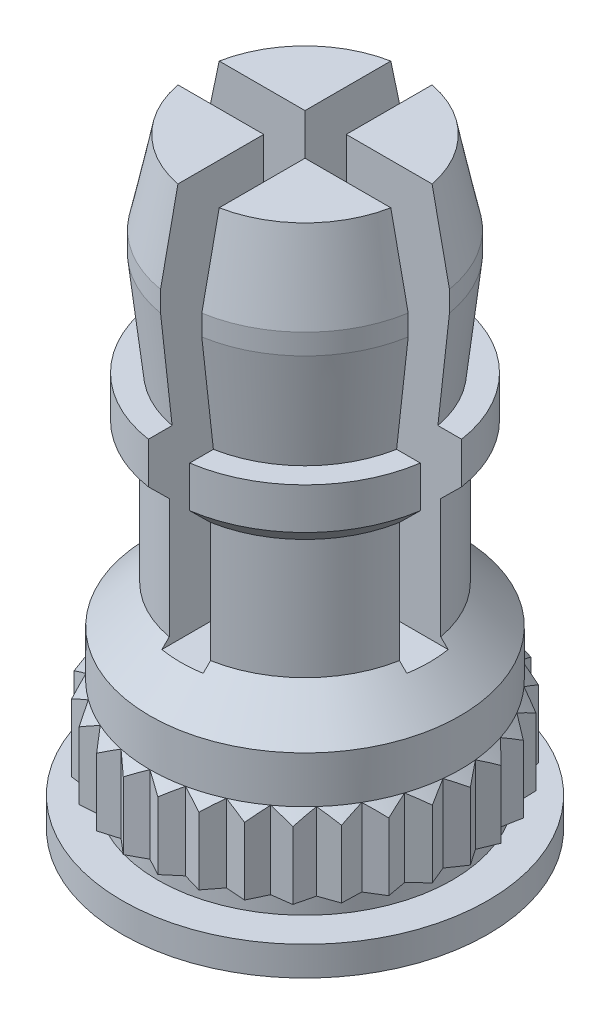
SolidWorks part; units mm, degrees
revolve "Body" add sketch "BodySke" angle 360 about L9
sketch "BodySke" plane through (0, 0, 0) normal (0, 0, 1) x (1, 0, 0)
  line L0 (2.5578, 0) -> (2.5578, 0.381)
  line L1 (2.6924, 2.5354) -> (2.0295, 3.1984)
  line L2 (2.8702, 1.5494) -> (2.6924, 1.7272)
  line L3 (2.0295, 3.1984) -> (2.0295, 5.2756)
  line L4 (0, -0.508) -> (3.175, -0.508)
  line L5 (3.175, -0.508) -> (3.175, 0)
  line L6 (3.175, 0) -> (2.5578, 0)
  line L7 (2.3876, 5.6337) -> (2.3876, 6.35)
  line L8 (2.6924, 1.7272) -> (2.6924, 2.5354)
  line L9 (0, -0.508) -> (0, 17.145) construction
  line L10 (2.3876, 6.35) -> (1.9812, 6.35)
  line L11 (1.9812, 6.35) -> (2.1793, 8.1407)
  line L12 (2.1793, 8.1407) -> (2.1793, 8.4988)
  line L13 (2.1793, 8.4988) -> (1.8821, 9.9314)
  line L14 (1.8821, 9.9314) -> (0, 9.9314)
  line L15 (2.5578, 0.381) -> (2.8702, 0.381)
  line L16 (2.8702, 0.381) -> (2.8702, 1.5494)
  line L17 (0, 9.9314) -> (0, -0.508)
  line L19 (2.3876, 5.6337) -> (2.0295, 5.2756)
  dimension "H_dia" = 6.35
  dimension "C_dia" = 5.3848
  dimension "Clinch_dia" = 5.7404
  dimension "Groove_dia" = 5.1156
  dimension "T_ht" = 0.508
  dimension "Groove_wid" = 0.381
  dimension "Clinch_lim" = 1.3462
  dimension "Length" = 6.35
  dimension "D_ht" = 3.5814
  dimension "D4" = 45
  dimension "Neck_dia" = 4.0589
  dimension "B_dia" = 4.7752
  dimension "B_ht" = 0.7163
  dimension "Panel_dia" = 3.9624
  dimension "Slip_dia" = 4.3586
  dimension "Tip_dia" = 3.7643
  dimension "Grip_ht" = 1.7907
  dimension "Slip_ht" = 0.3581
  dimension "Neck_len" = 3.1516
ref_plane "Plane1" through (0, 0, 0) normal (0, 0, 1) x (1, 0, 0)
ref_plane "Plane2" through (0, 0, 0) normal (0, 1, 0) x (1, 0, 0)
ref_plane "Plane3" through (0, 0, 0) normal (1, 0, 0) x (0, 0, -1)
sketch "SlitCutSke" plane through (0, 9.9314, 0) normal (0, 1, 0) x (-1, 0, 0)
  line L0 (-2.6685, 0.3581) -> (2.6685, 0.3581)
  line L1 (2.6685, -0.3581) -> (-2.6685, -0.3581)
  line L2 (-2.6685, 0.3581) -> (-2.6685, -0.3581)
  line L3 (2.6685, 0.3581) -> (2.6685, -0.3581)
  line L4 (-4.064, 0) -> (4.064, 0) construction
  circle A1 centre (0, 0) radius 2.6924 construction
extrude "SlitCut" cut sketch "SlitCutSke" against normal blind 6.86
pattern_circular "SlitCutPat" count 2 every 90 about axis through (0, -0.508, 0) along (0, 1, 0) of "SlitCut"
ref_plane "Plane4" through (0, -0.5486, 0) normal (0, 1, 0) x (-1, 0, 0)
sketch "CliRinCutSke" plane through (0, 0.381, 0) normal (0, -1, 0) x (1, 0, 0)
  line L0 (0.3, 2.8545) -> (0, 2.6924)
  line L1 (0, 2.6924) -> (-0.3, 2.8545)
  line L2 (0, 0) -> (0, 5.842) construction
  arc A1 (0.3, 2.8545) -> (-0.3, 2.8545) centre (0, 0) ccw
  circle A2 centre (0, 0) radius 2.6924 construction
  dimension "Clinch_dia" = 5.7404
  dimension "Angle" = 12
extrude "ClinchCut" cut sketch "CliRinCutSke" against normal blind 1.3462
pattern_circular "ClinchCutPat" count 30 every 12 about axis through (0, -0.508, 0) along (0, 1, 0) of "ClinchCut"
equation "' \"Panel_dia@BodySke\" = 0.156"
equation "' \"Length@BodySke\" = 0.25"
equation "' \"B_dia@BodySke\" = 0.188"
equation "' \"C_dia@BodySke\" = 0.212"
equation "' \"D_ht@BodySke\" = 0.141"
equation "' \"H_dia@BodySke\" = 0.25"
equation "' \"T_ht@BodySke\" = 0.02"
equation "' \"Clinch_dia@BodySke\" = 0.226"
equation "\"Tip_dia@BodySke\" = \"Panel_dia@BodySke\" * 0.95"
equation "\"Slip_dia@BodySke\" = \"Panel_dia@BodySke\" * 1.1"
equation "\"Slip_ht@BodySke\" = \"D_ht@BodySke\" * 0.1"
equation "\"Grip_ht@BodySke\" = \"D_ht@BodySke\" * 0.5"
equation "\"B_ht@BodySke\" = \"B_dia@BodySke\" * 0.15"
equation "\"Neck_dia@BodySke\" = \"B_dia@BodySke\" * 0.85"
equation "\"Neck_len@BodySke\" = \"B_dia@BodySke\" * 0.66"
equation "\"Groove_dia@BodySke\" = \"C_dia@BodySke\" * 0.95"
equation "\"Groove_wid@BodySke\" = \"T_ht@BodySke\" * 0.75"
equation "\"Width@SlitCutSke\" = \"B_ht@BodySke\""
equation "\"Depth@SlitCut\" = \"D_ht@BodySke\" + \"Neck_len@BodySke\" + 0.005"
equation "\"Clinch_lim@BodySke\" = \"C_dia@BodySke\" * 0.25"
equation "\"Count@ClinchCutPat\" = 30"
equation "\"Angle@ClinchCutPat\" = 360 / \"Count@ClinchCutPat\""
equation "\"Angle@CliRinCutSke\" = 360 / \"Count@ClinchCutPat\""
equation "\"Clinch_dia@CliRinCutSke\" = \"Clinch_dia@BodySke\""
equation "\"Clinch_minor@CliRinCutSke\" = \"C_dia@BodySke\""
equation "\"Depth@ClinchCut\" = \"Clinch_lim@BodySke\""
